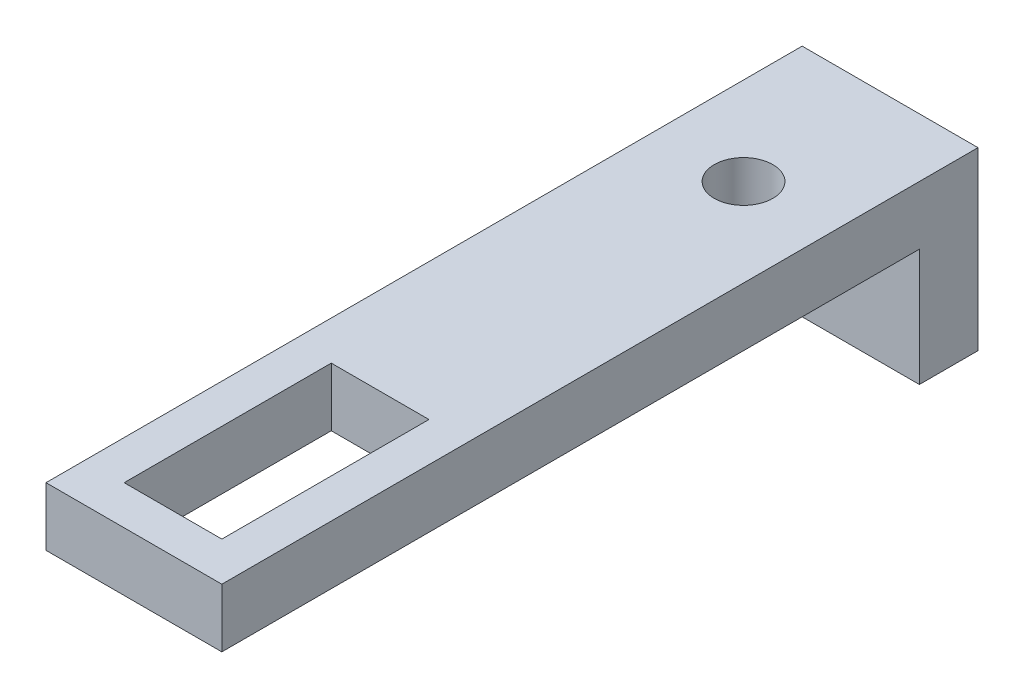
SolidWorks part; units mm, degrees
material "ABS"
ref_plane "Front Plane" through (0, 0, 0) normal (0, 0, 1) x (1, 0, 0)
ref_plane "Top Plane" through (0, 0, 0) normal (0, 1, 0) x (1, 0, 0)
ref_plane "Right Plane" through (0, 0, 0) normal (1, 0, 0) x (0, 0, -1)
sketch "Sketch1" plane through (0, 0, 0) normal (0, 1, 0) x (1, 0, 0)
  line L0 (-4.5, 0) -> (-4.5, -35.7) construction
  line L1 (0, 0) -> (-9, 0)
  line L2 (0, 0) -> (0, -35.7)
  line L3 (0, -35.7) -> (-9, -35.7)
  line L4 (-9, 0) -> (-9, -35.7)
  line L5 (-4.5, -4.5) -> (-4.5, -32.7) construction
  line L6 (-7, -32.7) -> (-7, -33.7)
  line L7 (-7, -32.7) -> (-2, -32.7) construction
  line L8 (-7, -32.7) -> (-7, -23.1)
  line L9 (-7, -23.1) -> (-2, -23.1)
  line L10 (-2, -32.7) -> (-2, -23.1)
  line L11 (-7, -33.7) -> (-2, -33.7)
  line L12 (-2, -33.7) -> (-2, -32.7)
  circle A0 centre (-4.5, -4.5) radius 1.5
  dimension "D3" = 3
  dimension "D1" = 9
  dimension "D2" = 4.5
  dimension "D4" = 28.2
  dimension "D5" = 3
  dimension "D6" = 9.6
  dimension "D7" = 5
  dimension "D8" = 2
  dimension "D9" = 1
  dimension "D10" = 2
extrude "Boss-Extrude1" add sketch "Sketch1" along normal blind 3
sketch "Sketch2" plane through (0, 3, 0) normal (0, 1, 0) x (1, 0, 0)
  line L1 (-9, 0) -> (0, 0)
  line L2 (-9, 0) -> (-9, 3)
  line L3 (-9, 3) -> (0, 3)
  line L4 (0, 0) -> (0, 3)
  dimension "D1" = 3
extrude "Boss-Extrude2" add sketch "Sketch2" against normal blind 9
